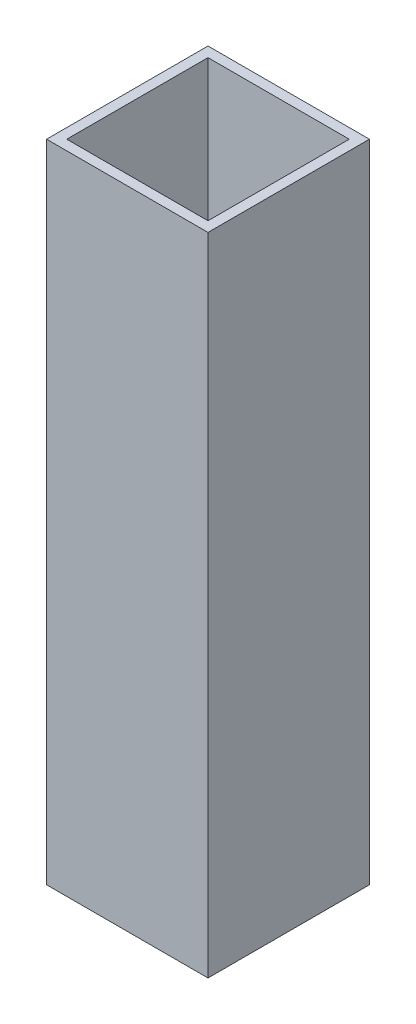
SolidWorks part; units mm, degrees
ref_plane "Front Plane" through (0, 0, 0) normal (0, 0, 1) x (1, 0, 0)
ref_plane "Top Plane" through (0, 0, 0) normal (0, 1, 0) x (1, 0, 0)
ref_plane "Right Plane" through (0, 0, 0) normal (1, 0, 0) x (0, 0, -1)
sketch "Sketch1" plane through (0, 0, 0) normal (0, 1, 0) x (1, 0, 0)
  line L1 (12.7, -12.7) -> (-12.7, -12.7)
  line L2 (12.7, -12.7) -> (12.7, 12.7)
  line L3 (12.7, 12.7) -> (-12.7, 12.7)
  line L4 (-12.7, -12.7) -> (-12.7, 12.7)
  line L5 (12.7, -12.7) -> (-12.7, 12.7) construction
  line L6 (12.7, 12.7) -> (-12.7, -12.7) construction
  line L7 (11.1125, -11.1125) -> (-11.1125, -11.1125)
  line L8 (11.1125, -11.1125) -> (11.1125, 11.1125)
  line L9 (11.1125, 11.1125) -> (-11.1125, 11.1125)
  line L10 (-11.1125, -11.1125) -> (-11.1125, 11.1125)
  line L11 (11.1125, -11.1125) -> (-11.1125, 11.1125) construction
  line L12 (11.1125, 11.1125) -> (-11.1125, -11.1125) construction
  point P0 (0, 0)
  point P6 (0, 0)
  dimension "D1" = 25.4
  dimension "D2" = 25.4
  dimension "D3" = 1.5875
  dimension "D4" = 1.5875
extrude "Boss-Extrude1" add sketch "Sketch1" along normal blind 101.6
